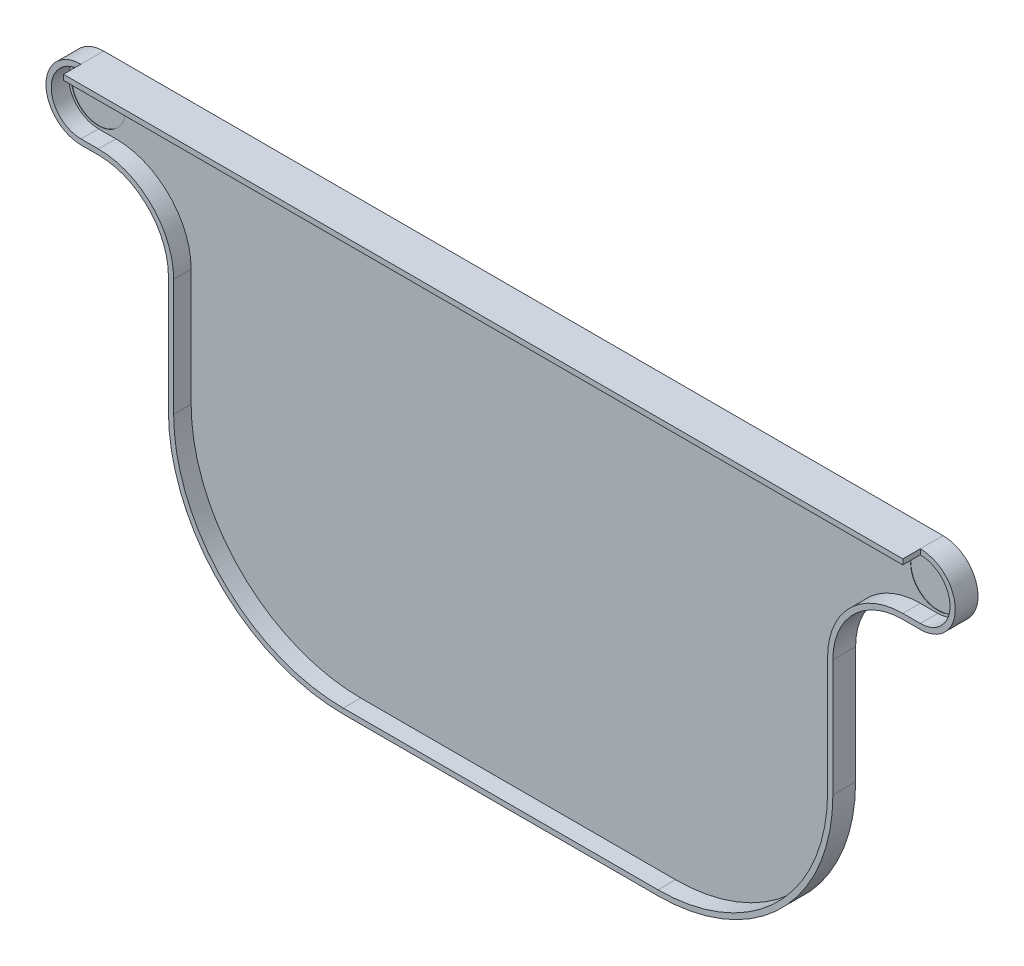
SolidWorks part; units mm, degrees
ref_plane "Front Plane" through (0, 0, 0) normal (0, 0, 1) x (1, 0, 0)
ref_plane "Top Plane" through (0, 0, 0) normal (0, 1, 0) x (1, 0, 0)
ref_plane "Right Plane" through (0, 0, 0) normal (1, 0, 0) x (0, 0, -1)
sketch "Sketch1" plane through (0, 0, 0) normal (0, 0, 1) x (1, 0, 0)
  line L0 (-240, -28.0856) -> (-230, -28.0856)
  line L1 (-240, 11.9144) -> (240, 11.9144)
  line L2 (-190, -68.0856) -> (-190, -135)
  line L3 (0, -235) -> (0, -28.0856) construction
  line L4 (-90, -235) -> (90, -235)
  line L5 (0, -28.0856) -> (0, 11.9144) construction
  line L6 (190, -68.0856) -> (190, -135)
  line L7 (240, -28.0856) -> (230, -28.0856)
  arc A0 (-240, 11.9144) -> (-240, -28.0856) centre (-240, -8.0856) ccw
  arc A1 (-190, -135) -> (-90, -235) centre (-90, -135) ccw
  arc A2 (-230, -28.0856) -> (-190, -68.0856) centre (-230, -68.0856) cw
  arc A3 (230, -28.0856) -> (190, -68.0856) centre (230, -68.0856) ccw
  arc A4 (190, -135) -> (90, -235) centre (90, -135) cw
  arc A5 (240, 11.9144) -> (240, -28.0856) centre (240, -8.0856) cw
  dimension "D1" = 20
  dimension "D2" = 100
  dimension "D5" = 40
  dimension "D3" = 190
  dimension "D4" = 235
extrude "Boss-Extrude1" add sketch "Sketch1" along normal blind 3
sketch "Sketch2" plane through (0, 0, 3) normal (0, 0, 1) x (1, 0, 0)
  line L1 (-240, 8.9144) -> (240, 8.9144)
  line L2 (-240, 8.9144) -> (-240, 11.9144)
  line L3 (-240, 11.9144) -> (240, 11.9144)
  line L4 (240, 8.9144) -> (240, 11.9144)
  line L7 (240, 11.9144) -> (-240, 11.9144) construction
  dimension "D1" = 3
  dimension "D2" = 240
  dimension "D3" = 240
extrude "Boss-Extrude2" add sketch "Sketch2" along normal blind 20
sketch "Sketch3" plane through (0, 0, 3) normal (0, 0, 1) x (1, 0, 0)
  line L0 (0, 0) -> (0, -114.1953) construction
  circle A0 centre (-240, -8.0856) radius 15.5
  circle A1 centre (240, -8.0856) radius 15.5
  dimension "D1" = 31
extrude "Cut-Extrude1" cut sketch "Sketch3" against normal blind 0.2
sketch "Sketch4" plane through (-240, 0, 0) normal (-1, 0, 0) x (0, 0, 1)
  line L0 (3, -28.0856) -> (3, 11.9144) construction
  line L4 (3, 11.9144) -> (3, 8.9144)
  line L5 (3, 8.9144) -> (23, 8.9144)
  line L6 (23, 8.9144) -> (23, 11.9144)
  line L7 (23, 11.9144) -> (3, 11.9144)
  line L8 (3, 11.9144) -> (3, 8.9144)
  line L9 (3, 8.9144) -> (13, 8.9144)
  line L10 (13, 8.9144) -> (13, 11.9144)
  line L11 (13, 11.9144) -> (3, 11.9144)
  dimension "D2" = 10
  dimension "D1" = 0
sketch "Sketch5" plane through (0, 0, 3) normal (0, 0, 1) x (1, 0, 0)
  line L0 (-240, -28.0856) -> (-230, -28.0856) construction
  line L1 (-190, -68.0856) -> (-190, -135) construction
  line L2 (-90, -235) -> (90, -235) construction
  line L3 (190, -135) -> (190, -68.0856) construction
  line L4 (230, -28.0856) -> (240, -28.0856) construction
  line L5 (-240, -28.0856) -> (-230, -28.0856)
  line L6 (-190, -68.0856) -> (-190, -135)
  line L7 (-90, -235) -> (90, -235)
  line L8 (190, -135) -> (190, -68.0856)
  line L9 (230, -28.0856) -> (240, -28.0856)
  arc A0 (-240, 11.9144) -> (-240, -28.0856) centre (-240, -8.0856) ccw construction
  arc A1 (-190, -68.0856) -> (-230, -28.0856) centre (-230, -68.0856) ccw construction
  arc A2 (-190, -135) -> (-90, -235) centre (-90, -135) ccw construction
  arc A3 (90, -235) -> (190, -135) centre (90, -135) ccw construction
  arc A4 (230, -28.0856) -> (190, -68.0856) centre (230, -68.0856) ccw construction
  arc A5 (240, -28.0856) -> (240, 11.9144) centre (240, -8.0856) ccw construction
  arc A6 (-240, 11.9144) -> (-240, -28.0856) centre (-240, -8.0856) ccw
  arc A7 (-190, -68.0856) -> (-230, -28.0856) centre (-230, -68.0856) ccw
  arc A8 (-190, -135) -> (-90, -235) centre (-90, -135) ccw
  arc A9 (90, -235) -> (190, -135) centre (90, -135) ccw
  arc A10 (230, -28.0856) -> (190, -68.0856) centre (230, -68.0856) ccw
  arc A11 (240, -28.0856) -> (240, 11.9144) centre (240, -8.0856) ccw
sweep "Sweep1" add profiles "Sketch4" path "Sketch5"
